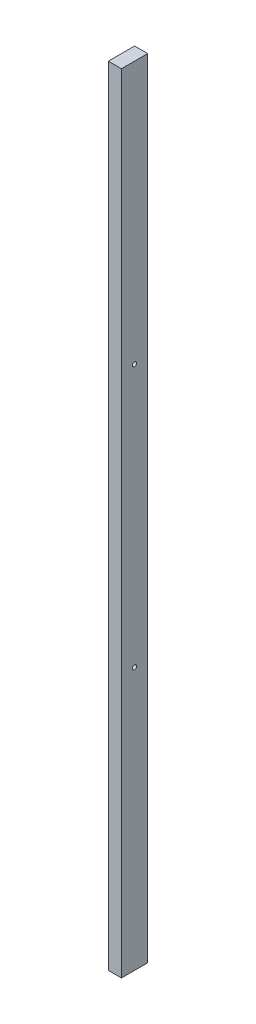
SolidWorks part; units mm, degrees
ref_plane "Спереди" through (0, 0, 0) normal (0, 0, 1) x (1, 0, 0)
ref_plane "Сверху" through (0, 0, 0) normal (0, 1, 0) x (1, 0, 0)
ref_plane "Справа" through (0, 0, 0) normal (1, 0, 0) x (0, 0, -1)
other "Configuration Table"
sketch "Эскиз1" plane through (0, 0, 0) normal (0, 1, 0) x (1, 0, 0)
  line L1 (12.5, 25) -> (-12.5, 25)
  line L2 (12.5, 25) -> (12.5, -25)
  line L3 (12.5, -25) -> (-12.5, -25)
  line L4 (-12.5, 25) -> (-12.5, -25)
  line L5 (12.5, 25) -> (-12.5, -25) construction
  line L6 (12.5, -25) -> (-12.5, 25) construction
  point P0 (0, 0)
extrude "Бобышка-Вытянуть1" add sketch "Эскиз1" along normal blind 1500
sketch "Эскиз2" plane through (-12.5, 0, 0) normal (-1, 0, 0) x (0, 0, 1)
  line L0 (0, 500) -> (0, 1000) construction
  line L2 (0, 0) -> (0, 500) construction
  line L3 (0, 1000) -> (0, 1500) construction
  line L4 (-25, 1500) -> (25, 1500) construction
  circle A0 centre (0, 1000) radius 4
  circle A1 centre (0, 500) radius 4
extrude "Вырез-Вытянуть1" cut sketch "Эскиз2" against normal blind 1500
